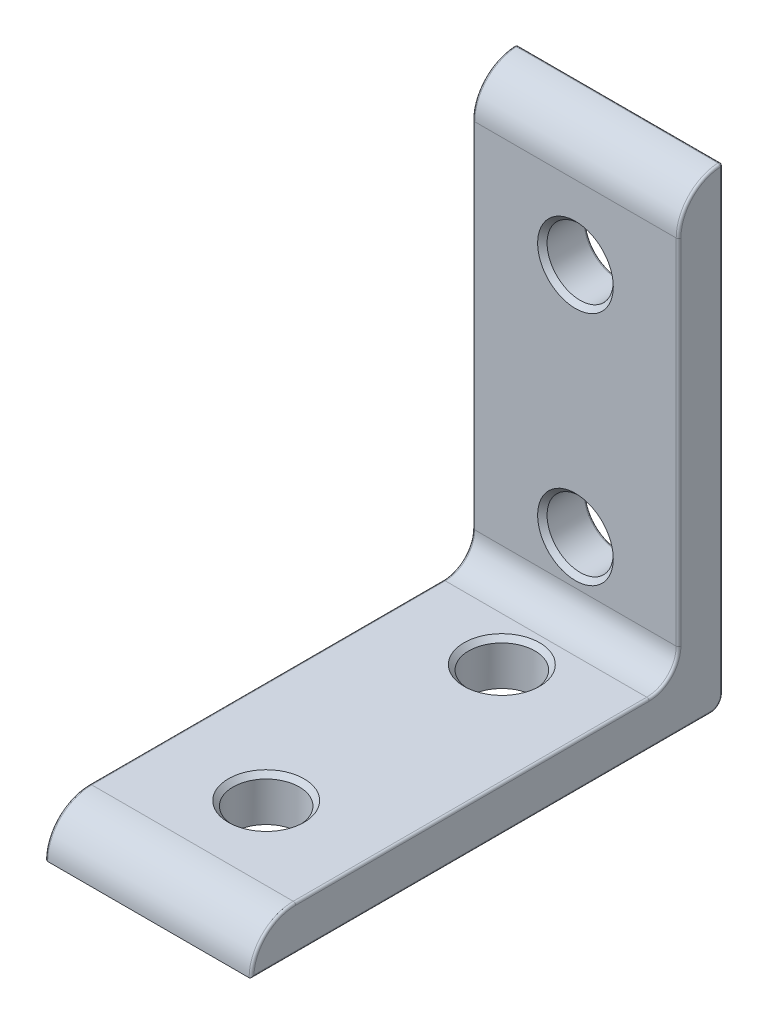
SolidWorks part; units mm, degrees
ref_plane "Front Plane" through (0, 0, 0) normal (0, 0, 1) x (1, 0, 0)
ref_plane "Top Plane" through (0, 0, 0) normal (0, 1, 0) x (1, 0, 0)
ref_plane "Right Plane" through (0, 0, 0) normal (1, 0, 0) x (0, 0, -1)
sketch "Sketch1" plane through (0, 0, 0) normal (0, 0, 1) x (1, 0, 0)
  line L0 (-11.1125, -25.4) -> (11.1125, -25.4) construction
  line L1 (0, -25.4) -> (0, 25.4) construction
  line L2 (-11.1125, 25.4) -> (11.1125, 25.4) construction
  dimension "Width" = 22.225
  dimension "Length" = 50.8
sketch "Sketch2" plane through (0, 0, 0) normal (1, 0, 0) x (0, 0, -1)
  line L0 (-46.0375, -25.4) -> (4.7625, -25.4) construction
  line L1 (0, -25.4) -> (0, 25.4) construction
  line L2 (4.7625, -25.4) -> (4.7625, 25.4) construction
  line L3 (0, 20.6375) -> (0, -17.4625)
  line L4 (-3.175, -20.6375) -> (-41.275, -20.6375)
  line L5 (4.7625, -12.7) -> (0, -12.7) construction
  line L6 (-7.9375, -25.4) -> (-7.9375, -20.6375) construction
  line L7 (4.7625, -9.1313) -> (4.7625, -16.2687)
  line L8 (-11.5062, -25.4) -> (-4.3688, -25.4)
  line L9 (4.7625, -12.7) -> (12.7, -12.7) construction
  line L10 (12.7, -9.525) -> (12.7, -15.875) construction
  line L11 (4.7625, 16.2687) -> (4.7625, 9.1313)
  line L12 (-36.9062, -25.4) -> (-29.7688, -25.4)
  arc A0 (4.7625, 25.4) -> (0, 20.6375) centre (4.7625, 20.6375) ccw
  arc A1 (0, -17.4625) -> (-3.175, -20.6375) centre (-3.175, -17.4625) cw
  arc A2 (-41.275, -20.6375) -> (-46.0375, -25.4) centre (-41.275, -25.4) ccw
  point P28 (-33.3375, -25.4)
  point P30 (4.7625, 12.7)
  dimension "Bracket End Radius" = 4.7625
  dimension "Bracket Corner Radius" = 3.175
  dimension "Bracket Thickness" = 4.7625
  dimension "Mounting Hole Diameter" = 7.1374
  dimension "Mounting Hole Center Offset" = 12.7
  dimension "D3" = 12.7
  dimension "Mounting Fastener Thread Length" = 12.7
  dimension "Mounting Fastener Thread Size" = 6.35
  dimension "Mounting Hole CtoC" = 25.4
  dimension "D5" = 25.4
sketch "Sketch3" plane through (0, 0, 0) normal (1, 0, 0) x (0, 0, -1)
  line L0 (-3.175, -20.6375) -> (-41.275, -20.6375) construction
  line L1 (0, 20.6375) -> (0, -17.4625) construction
  line L2 (-3.175, -20.6375) -> (-41.275, -20.6375)
  line L3 (0, 20.6375) -> (0, -17.4625)
  line L4 (-46.0375, -25.4) -> (4.7625, -25.4)
  line L5 (4.7625, -25.4) -> (4.7625, 25.4)
  arc A0 (-41.275, -20.6375) -> (-46.0375, -25.4) centre (-41.275, -25.4) ccw construction
  arc A1 (-3.175, -20.6375) -> (0, -17.4625) centre (-3.175, -17.4625) ccw construction
  arc A2 (4.7625, 25.4) -> (0, 20.6375) centre (4.7625, 20.6375) ccw construction
  arc A3 (-41.275, -20.6375) -> (-46.0375, -25.4) centre (-41.275, -25.4) ccw
  arc A4 (-3.175, -20.6375) -> (0, -17.4625) centre (-3.175, -17.4625) ccw
  arc A5 (4.7625, 25.4) -> (0, 20.6375) centre (4.7625, 20.6375) ccw
extrude "Boss-Extrude1" add sketch "Sketch3" against normal up to vertex (11.1125 mm away) from vertex at 11.1125 starting at point (11.1125, -25.4, 0)
fillet "Fillet1" radius 1.2716 1 edges at (0, -25.4, -4.7625)
sketch "Sketch4" plane through (0, 0, 0) normal (0, 0, 1) x (1, 0, 0)
  line L1 (0, -17.4625) -> (0, 20.6375) construction
  line L2 (-11.1125, -17.4625) -> (11.1125, -17.4625) construction
  line L3 (-11.1125, 20.6375) -> (11.1125, 20.6375) construction
  line L4 (0, 16.2687) -> (0, 9.1313) construction
  circle A0 centre (0, 12.7) radius 3.5687
  circle A1 centre (0, -12.7) radius 3.5687
  point P21 (0, 12.7)
extrude "Cut-Extrude1" cut sketch "Sketch4" against normal through all
sketch "Sketch6" plane through (0, -20.6375, 0) normal (0, 1, 0) x (1, 0, 0)
  line L0 (0, -3.175) -> (0, -41.275) construction
  line L1 (0, -36.9062) -> (0, -29.7688) construction
  circle A0 centre (0, -7.9375) radius 3.5687
  circle A1 centre (0, -33.3375) radius 3.5687
extrude "Cut-Extrude3" cut sketch "Sketch6" against normal blind 7.874
chamfer "Chamfer1" distance 0.508 angle 45 4 edges at (3.5687, 12.7, 0) (-3.5687, -12.7, 0) (0, -20.6375, 36.9062) (0, -20.6375, 11.5062)
fillet "Fillet2" radius 0.254 19 edges at (-11.1125, -25.4, 21.2733) (-11.1125, -25.0276, -4.3901) (11.1125, -25.4, 21.2733) (11.1125, -25.0276, -4.3901) (-11.1125, 24.0051, -1.3949) (-11.1125, -22.0324, 44.6426) (-11.1125, -20.6375, 22.225) (-11.1125, -19.7076, 0.9299) (11.1125, 24.0051, -1.3949) (11.1125, -22.0324, 44.6426) (11.1125, -20.6375, 22.225) (11.1125, -19.7076, 0.9299) (0, 25.4, -4.7625) (-11.1125, 0.6358, -4.7625) (11.1125, 0.6358, -4.7625) (-3.5687, -12.7, -4.7625) (3.5687, 12.7, -4.7625) (-11.1125, 1.5875, 0) (11.1125, 1.5875, 0)
equation "\"D3@Sketch2\" = \"Mounting Hole Center Offset@Sketch2\""
equation "\"D5@Sketch2\"=\"Mounting Hole CtoC@Sketch2\""
equation "\"D1@Fillet1\"=\"Bracket Thickness@Sketch2\"*.267"
